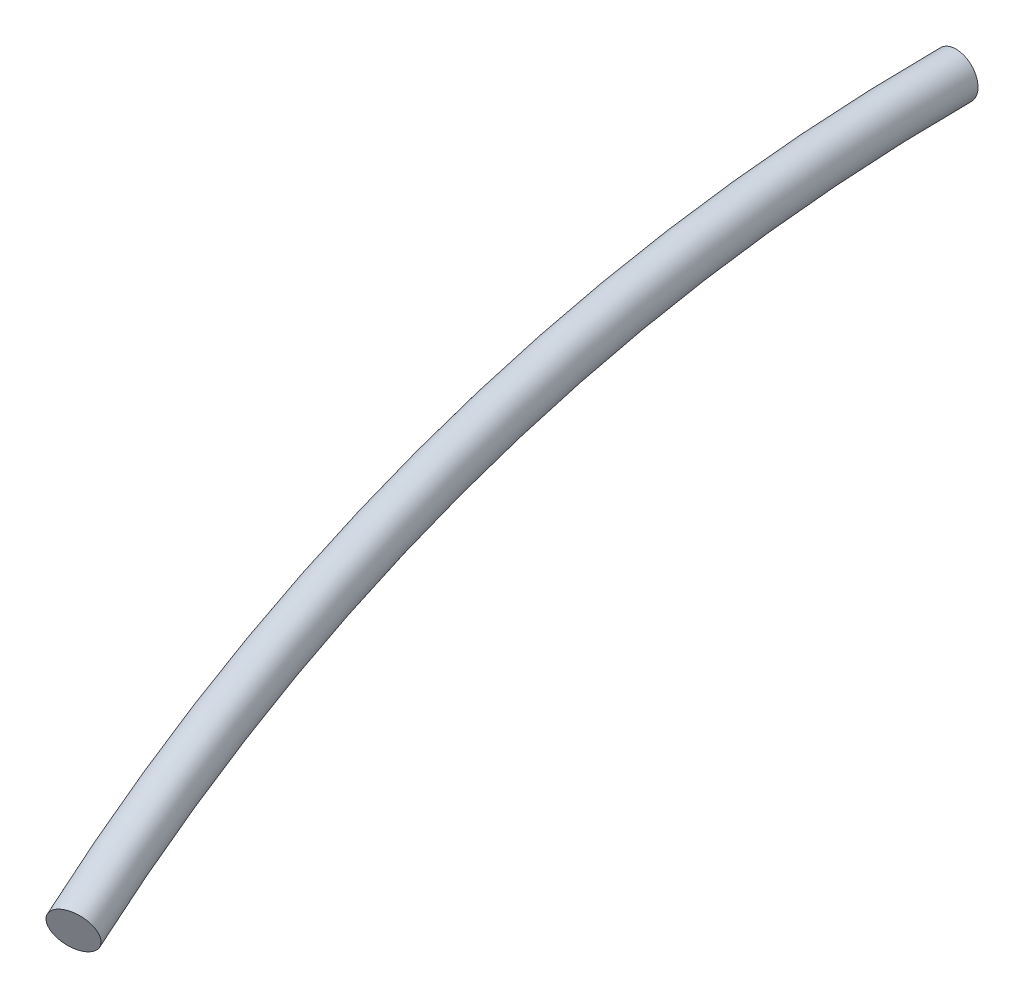
SolidWorks part; units mm, degrees
ref_plane "Front" through (0, 0, 0) normal (0, 0, 1) x (1, 0, 0)
ref_plane "Top" through (0, 0, 0) normal (0, 1, 0) x (1, 0, 0)
ref_plane "Right" through (0, 0, 0) normal (1, 0, 0) x (0, 0, -1)
sketch "Sketch1" plane through (0, 0, 0) normal (0, 0, 1) x (1, 0, 0)
  circle A0 centre (-6172.5411, -14873.7138) radius 50.8
ref_plane "Plane1" through (-10809.9971, -9711.9295, 0) normal (0.7439, 0.6683, 0) x (-0.6173, 0.6871, -0.3833)
sketch "Sketch2" plane through (-10809.9971, -9711.9295, 0) normal (0.7439, 0.6683, 0) x (-0.6173, 0.6871, -0.3833)
  line L0 (-7772.034, -658.3888) -> (-8502.6199, 47.7842) construction
  line L1 (-6409.0236, -2659.7803) -> (-8600.5772, 2621.0013) construction
  arc A0 (-6409.0236, -2659.7803) -> (-7772.034, -658.3888) centre (-11915.3396, -4944.9319) ccw
  point P3 (-7628.3643, -802.0734)
  point P5 (-7196.6552, -1301.3826)
  point P6 (-6862.8225, -1780.5197)
  point P7 (-6577.4682, -2290.019)
  dimension "D1" = 2438.4
  dimension "D2" = 203.2
  dimension "D3" = 660.4
  dimension "D4" = 584.2
  dimension "D5" = 584.2
sweep "Sweep1" add profiles "Sketch1" path "Sketch2"
